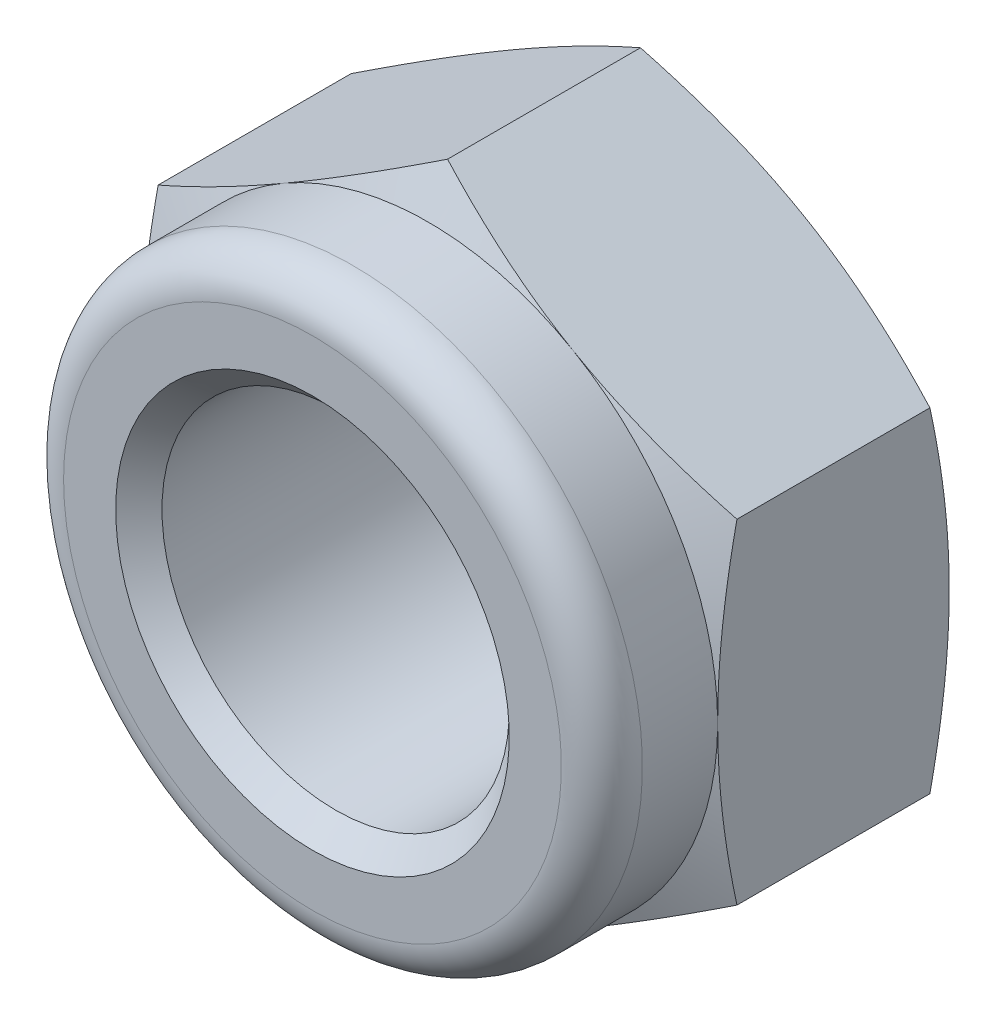
SolidWorks part; units mm, degrees
material "Plain Carbon Steel"
ref_plane "Front Plane" through (0, 0, 0) normal (0, 0, 1) x (1, 0, 0)
ref_plane "Top Plane" through (0, 0, 0) normal (0, 1, 0) x (1, 0, 0)
ref_plane "Right Plane" through (0, 0, 0) normal (1, 0, 0) x (0, 0, -1)
sketch "Sketch1" plane through (0, 0, 0) normal (0, 0, 1) x (1, 0, 0)
  line L1 (0, -5.7735) -> (5, -2.8868)
  line L2 (5, -2.8868) -> (5, 2.8868)
  line L3 (5, 2.8868) -> (0, 5.7735)
  line L4 (0, 5.7735) -> (-5, 2.8868)
  line L5 (-5, 2.8868) -> (-5, -2.8868)
  line L6 (-5, -2.8868) -> (0, -5.7735)
  circle A0 centre (0, 0) radius 5 construction
  circle A1 centre (0, 0) radius 3
  dimension "D2" = 6
  dimension "D1" = 10
extrude "Boss-Extrude1" add sketch "Sketch1" along normal blind 4
sketch "Sketch3" plane through (0, 0, 0) normal (0, 1, 0) x (0, 0, -1)
  line L0 (-4, 5) -> (-5.3, 5)
  line L1 (-4, -5) -> (-4, 0) construction
  line L2 (-6, 4.3) -> (-6, 3)
  line L3 (-6, 3) -> (-4, 3)
  line L5 (-4, 3) -> (-4, 5)
  line L6 (0, 0) -> (-2.4, 0) construction
  arc A0 (-5.3, 5) -> (-6, 4.3) centre (-5.3, 4.3) ccw
  dimension "D1" = 0.7
  dimension "D2" = 6
revolve "Revolve1" add sketch "Sketch3" angle 360 about L6
sketch "Sketch2" plane through (0, 0, 0) normal (1, 0, 0) x (0, 0, -1)
  line L0 (-4, 5.7735) -> (-4, 5)
  line L1 (-4, 2.8868) -> (-4, 4.3301) construction
  line L2 (-4, 5) -> (-3.6667, 5.7735)
  line L3 (-4, 5.7735) -> (0, 5.7735) construction
  line L4 (-3.6667, 5.7735) -> (-4, 5.7735)
  line L5 (-0.3333, 5.7735) -> (0, 5.7735)
  line L6 (0, 5.7735) -> (0, 5)
  line L7 (0, 2.8868) -> (0, 5.7735) construction
  line L8 (0, 5) -> (-0.3333, 5.7735)
  line L9 (-3.6667, 5.7735) -> (-3.3333, 5.7735) construction
  line L10 (-3.3333, 5.7735) -> (-3, 5.7735) construction
  line L11 (-3, 5.7735) -> (-2.6667, 5.7735) construction
  line L12 (-2.6667, 5.7735) -> (-2.3333, 5.7735) construction
  line L13 (-2.3333, 5.7735) -> (-2, 5.7735) construction
  line L14 (-2, 5.7735) -> (-1.6667, 5.7735) construction
  line L15 (-1.6667, 5.7735) -> (-1.3333, 5.7735) construction
  line L16 (-1.3333, 5.7735) -> (-1, 5.7735) construction
  line L17 (-1, 5.7735) -> (-0.6667, 5.7735) construction
  line L18 (0, 0) -> (-2.4, 0) construction
  line L20 (-6, 3) -> (-5.6, 3)
  line L21 (-5.6, 3) -> (-6, 3.4)
  line L22 (-6, 3.4) -> (-6, 3)
  line L23 (0, 3) -> (-0.4, 3)
  line L24 (0, -2.8868) -> (0, 2.8868) construction
  line L25 (-0.4, 3) -> (0, 3.4)
  line L26 (0, 3.4) -> (0, 3)
  line L27 (-6, 4.3) -> (-6, -4.3) construction
  line L28 (-3.2, 3) -> (-3.6, 3) construction
  line L29 (-3.6, 3) -> (-4, 3) construction
  line L30 (-3.2, 3) -> (-2.8, 3) construction
  line L31 (-2.8, 3) -> (-2.4, 3) construction
  line L32 (-2.4, 3) -> (-2, 3) construction
  line L33 (-2, 3) -> (-1.6, 3) construction
  line L34 (-1.6, 3) -> (-1.2, 3) construction
  line L35 (-1.2, 3) -> (-0.8, 3) construction
  line L36 (-0.8, 3) -> (-0.4, 3) construction
  line L37 (-0.6667, 5.7735) -> (-0.3333, 5.7735) construction
  line L38 (-4, 0) -> (-4, 2.8868) construction
  dimension "D1" = 10
revolve "Cut-Revolve1" cut sketch "Sketch2" angle 360 about L18
